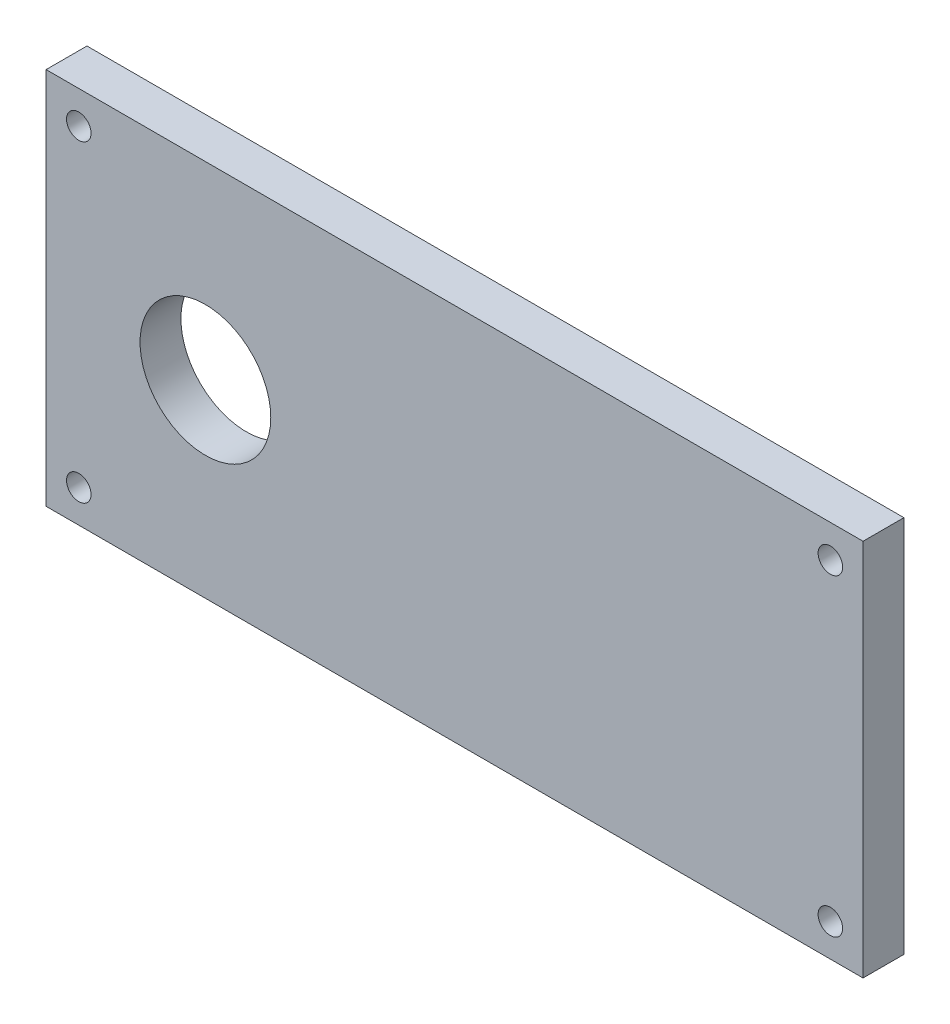
SolidWorks part; units mm, degrees
ref_plane "Front Plane" through (0, 0, 0) normal (0, 0, 1) x (1, 0, 0)
ref_plane "Top Plane" through (0, 0, 0) normal (0, 1, 0) x (1, 0, 0)
ref_plane "Right Plane" through (0, 0, 0) normal (1, 0, 0) x (0, 0, -1)
sketch "Sketch1" plane through (0, 0, 0) normal (0, 0, 1) x (1, 0, 0)
  line L0 (-1000, 0) -> (49000, 0) construction
  line L1 (0, -1000) -> (0, 49000) construction
  line L3 (-50, -23.15) -> (50, -23.15)
  line L4 (-50, -23.15) -> (-50, 23.15)
  line L5 (-50, 23.15) -> (50, 23.15)
  line L6 (50, -23.15) -> (50, 23.15)
  line L7 (-50, -23.15) -> (50, 23.15) construction
  line L8 (-50, 23.15) -> (50, -23.15) construction
  circle A1 centre (46, 19.15) radius 1.5
  circle A4 centre (-46, 19.15) radius 1.5
  circle A5 centre (46, -19.15) radius 1.5
  circle A6 centre (-46, -19.15) radius 1.5
  circle A8 centre (-30.5, 0) radius 8
  point P13 (0, 0)
  dimension "D1" = 3
  dimension "D2" = 49.8269
  dimension "D6" = 19.5
  dimension "D7" = 16
  dimension "D3" = 19.15
  dimension "D4" = 4
  dimension "D5" = 4
extrude "Boss-Extrude1" add sketch "Sketch1" along normal blind 5
